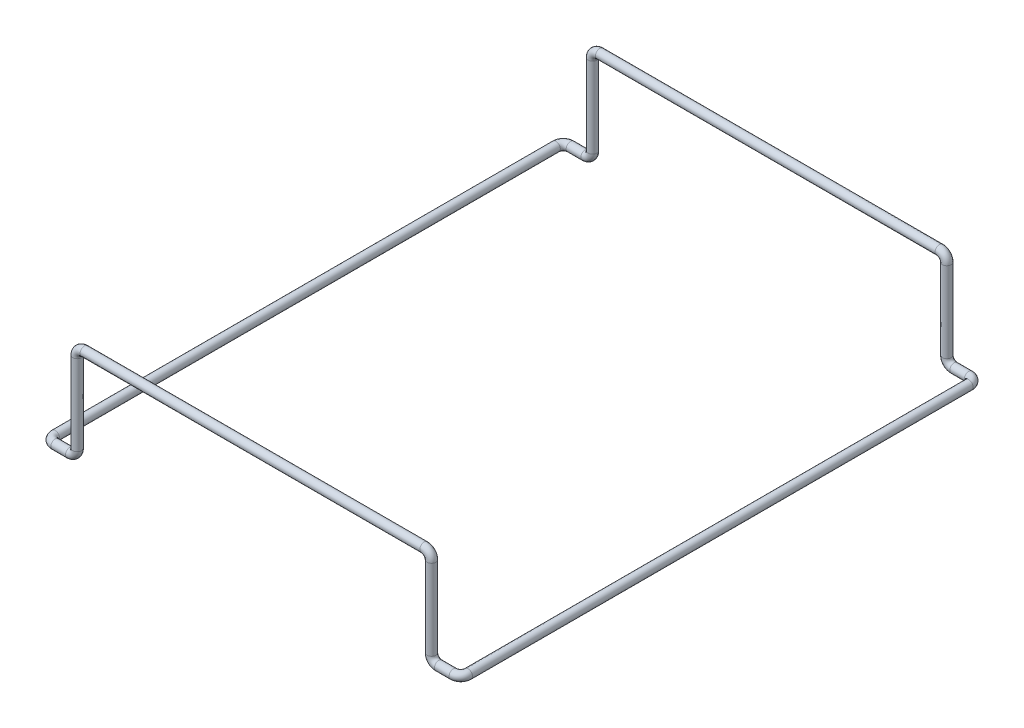
SolidWorks part; units mm, degrees
material "AISI 304"
ref_plane "Front Plane" through (0, 0, 0) normal (0, 0, 1) x (1, 0, 0)
ref_plane "Top Plane" through (0, 0, 0) normal (0, 1, 0) x (1, 0, 0)
ref_plane "Right Plane" through (0, 0, 0) normal (1, 0, 0) x (0, 0, -1)
sketch3d "3DSketch2"
  line L0 (0, 0, 5) -> (0, 0, 347)
  line L1 (5, 0, 0) -> (15, 0, 0)
  line L2 (5, 0, 352) -> (15, 0, 352)
  line L3 (20, 5, 352) -> (20, 60, 352)
  line L4 (20, 5, 0) -> (20, 60, 0)
  line L5 (25, 65, 0) -> (257, 65, 0)
  line L6 (25, 65, 352) -> (257, 65, 352)
  line L7 (262, 60, 352) -> (262, 5, 352)
  line L8 (262, 60, 0) -> (262, 5, 0)
  line L9 (267, 0, 352) -> (277, 0, 352)
  line L10 (267, 0, 0) -> (277, 0, 0)
  line L11 (282, 0, 347) -> (282, 0, 5)
  arc A0 (282, 0, 5) -> (277, 0, 0) centre (277, 0, 5) ccw
  arc A1 (282, 0, 347) -> (277, 0, 352) centre (277, 0, 347) ccw
  arc A2 (267, 0, 352) -> (262, 5, 352) centre (267, 5, 352) ccw
  arc A3 (267, 0, 0) -> (262, 5, 0) centre (267, 5, 0) ccw
  arc A4 (15, 0, 352) -> (20, 5, 352) centre (15, 5, 352) ccw
  arc A5 (25, 65, 352) -> (20, 60, 352) centre (25, 60, 352) ccw
  arc A6 (5, 0, 352) -> (0, 0, 347) centre (5, 0, 347) ccw
  arc A7 (5, 0, 0) -> (0, 0, 5) centre (5, 0, 5) ccw
  arc A8 (15, 0, 0) -> (20, 5, 0) centre (15, 5, 0) ccw
  arc A9 (20, 60, 0) -> (25, 65, 0) centre (25, 60, 0) ccw
  arc A10 (262, 60, 0) -> (257, 65, 0) centre (257, 60, 0) ccw
  arc A11 (262, 60, 352) -> (257, 65, 352) centre (257, 60, 352) ccw
  point P15 (282, 0, 0)
  point P16 (277, 5, 5)
  point P19 (282, 0, 352)
  point P20 (277, -5, 347)
  point P23 (262, 0, 352)
  point P24 (267, 5, 347)
  point P27 (262, 0, 0)
  point P28 (267, 5, -5)
  point P31 (20, 0, 352)
  point P32 (15, 5, 357)
  point P35 (20, 65, 352)
  point P36 (25, 60, 357)
  point P39 (0, 0, 352)
  point P40 (5, -5, 347)
  point P43 (0, 0, 0)
  point P44 (5, 5, 5)
  point P47 (20, 0, 0)
  point P48 (15, 5, 5)
  point P51 (20, 65, 0)
  point P52 (25, 60, -5)
  point P55 (262, 65, 0)
  point P56 (257, 60, 5)
  point P59 (262, 65, 352)
  point P60 (257, 60, 357)
  dimension "D12" = 5
  dimension "D13" = 5
  dimension "D14" = 5
  dimension "D15" = 5
  dimension "D1" = 352
  dimension "D2" = 20
  dimension "D3" = 20
  dimension "D4" = 65
  dimension "D5" = 65
  dimension "D6" = 242
  dimension "D7" = 242
  dimension "D8" = 65
  dimension "D9" = 65
  dimension "D10" = 20
  dimension "D11" = 20
ref_plane "Plane1" through (282, 0, 5) normal (0, 0, -1) x (-1, 0, 0)
sketch "Sketch1" plane through (282, 0, 5) normal (0, 0, -1) x (-1, 0, 0)
  circle A0 centre (0, 0) radius 3
  dimension "D1" = 6
sweep "Sweep1" add profiles "Sketch1" path "3DSketch2"
